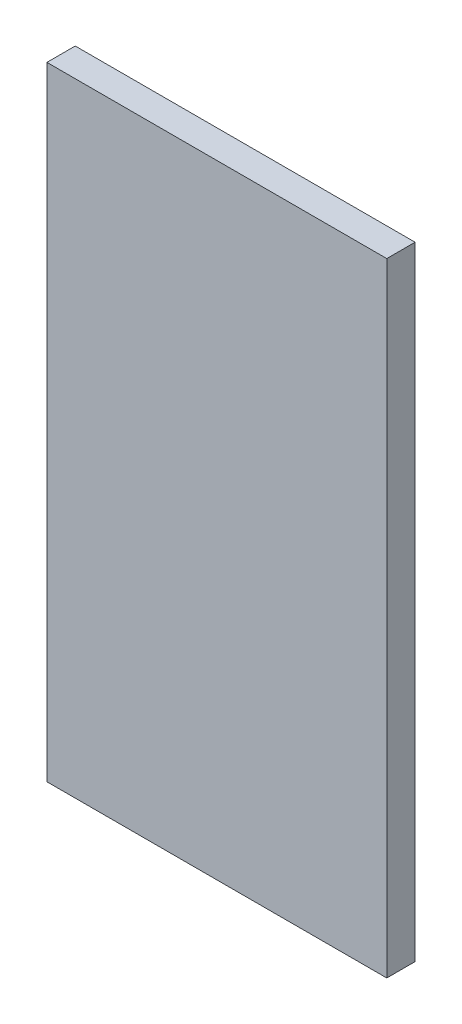
SolidWorks part; units mm, degrees
ref_plane "Front Plane" through (0, 0, 0) normal (0, 0, 1) x (1, 0, 0)
ref_plane "Top Plane" through (0, 0, 0) normal (0, 1, 0) x (1, 0, 0)
ref_plane "Right Plane" through (0, 0, 0) normal (1, 0, 0) x (0, 0, -1)
sketch "Sketch1" plane through (0, 0, 0) normal (0, 1, 0) x (1, 0, 0)
  line L1 (0, 0) -> (60, 0)
  line L2 (0, 0) -> (0, -5)
  line L3 (0, -5) -> (60, -5)
  line L4 (60, 0) -> (60, -5)
  dimension "D1" = 60
  dimension "D2" = 5
extrude "Boss-Extrude1" add sketch "Sketch1" along normal blind 110
